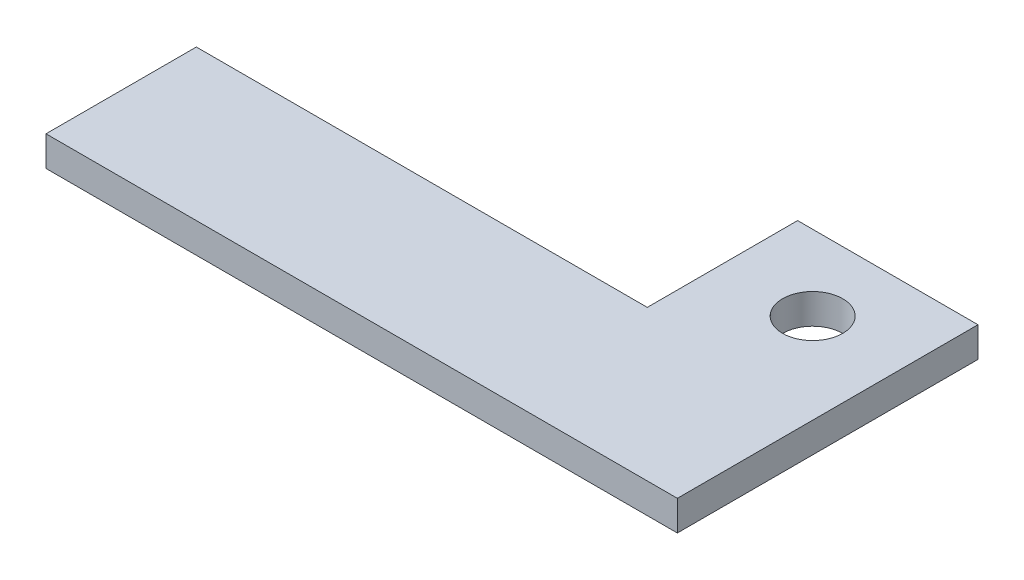
SolidWorks part; units mm, degrees
material "1060 Alloy"
ref_plane "Front Plane" through (0, 0, 0) normal (0, 0, 1) x (1, 0, 0)
ref_plane "Top Plane" through (0, 0, 0) normal (0, 1, 0) x (1, 0, 0)
ref_plane "Right Plane" through (0, 0, 0) normal (1, 0, 0) x (0, 0, -1)
sketch "Sketch1" plane through (0, 0, 0) normal (0, 1, 0) x (1, 0, 0)
  line L0 (0, 0) -> (-42, 0)
  line L1 (-42, 0) -> (-42, 10)
  line L2 (-42, 10) -> (-12, 10)
  line L3 (-12, 10) -> (-12, 20)
  line L4 (-12, 20) -> (0, 20)
  line L5 (0, 20) -> (0, 0)
  line L6 (-6, 15) -> (-6, 20) construction
  circle A0 centre (-6, 15) radius 2
  dimension "D2" = 4
  dimension "D1" = 12
  dimension "D3" = 20
  dimension "D4" = 5
  dimension "D5" = 10
  dimension "D6" = 42
extrude "Boss-Extrude1" add sketch "Sketch1" along normal blind 2
